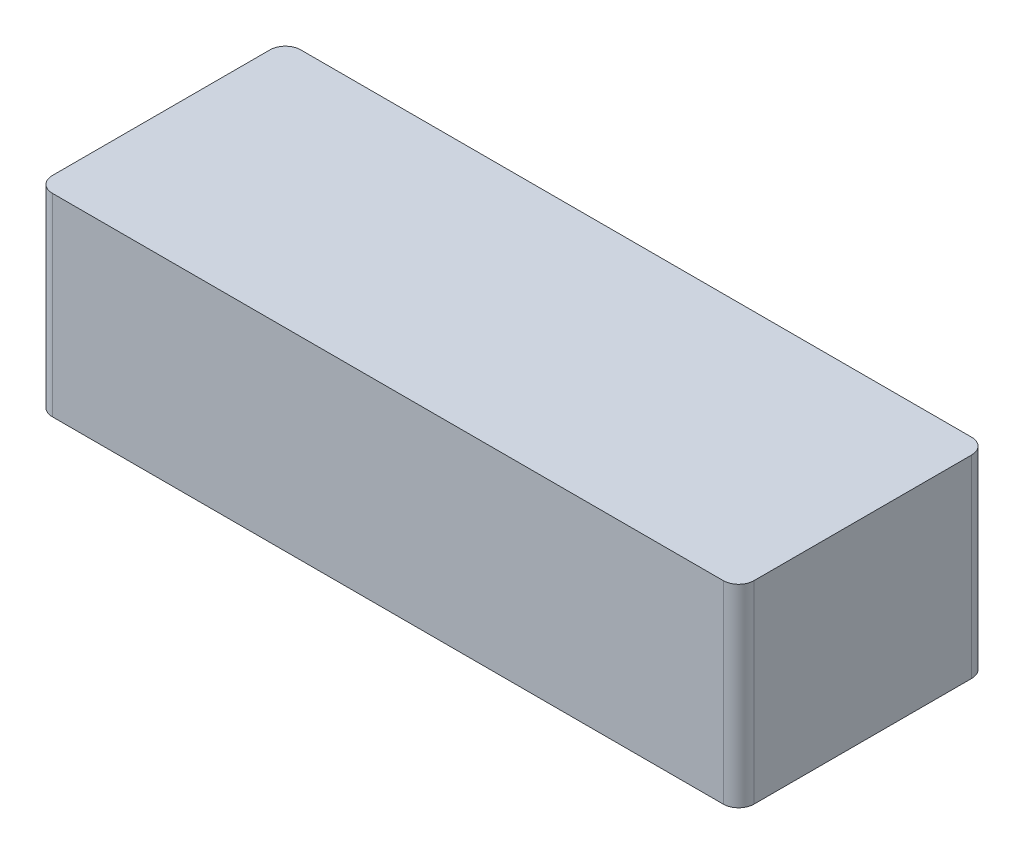
SolidWorks part; units mm, degrees
material "PA Type 6"
ref_plane "Front Plane" through (0, 0, 0) normal (0, 0, 1) x (1, 0, 0)
ref_plane "Top Plane" through (0, 0, 0) normal (0, 1, 0) x (1, 0, 0)
ref_plane "Right Plane" through (0, 0, 0) normal (1, 0, 0) x (0, 0, -1)
sketch "Sketch1" plane through (0, 0, 0) normal (0, 1, 0) x (1, 0, 0)
  line L0 (-68.5, -21.25) -> (-68.5, 21.25)
  line L1 (-65.5, -23.25) -> (65.5, -23.25) construction
  line L2 (-67.5, -21.25) -> (-67.5, 21.25) construction
  line L3 (-65.5, 23.25) -> (65.5, 23.25) construction
  line L4 (67.5, -21.25) -> (67.5, 21.25) construction
  line L5 (-67.5, -23.25) -> (67.5, 23.25) construction
  line L6 (-67.5, 23.25) -> (67.5, -23.25) construction
  line L7 (-65.5, 24.25) -> (65.5, 24.25)
  line L8 (68.5, -21.25) -> (68.5, 21.25)
  line L9 (-65.5, -24.25) -> (65.5, -24.25)
  arc A0 (65.5, 23.25) -> (67.5, 21.25) centre (65.5, 21.25) cw construction
  arc A1 (65.5, -23.25) -> (67.5, -21.25) centre (65.5, -21.25) ccw construction
  arc A2 (-65.5, -23.25) -> (-67.5, -21.25) centre (-65.5, -21.25) cw construction
  arc A3 (-67.5, 21.25) -> (-65.5, 23.25) centre (-65.5, 21.25) cw construction
  arc A4 (-68.5, 21.25) -> (-65.5, 24.25) centre (-65.5, 21.25) cw
  arc A5 (65.5, 24.25) -> (68.5, 21.25) centre (65.5, 21.25) cw
  arc A6 (65.5, -24.25) -> (68.5, -21.25) centre (65.5, -21.25) ccw
  arc A7 (-65.5, -24.25) -> (-68.5, -21.25) centre (-65.5, -21.25) cw
  point P0 (0, 0)
  dimension "D3" = 2
  dimension "D1" = 135
  dimension "D2" = 46.5
  dimension "D4" = 1
extrude "Boss-Extrude1" add sketch "Sketch1" along normal blind 31.5
shell "Shell1" thickness 1
sketch "Sketch2" plane through (0, 0, 0) normal (0, 1, 0) x (1, 0, 0)
  line L0 (-68.5, 21.25) -> (-68.5, 17)
  line L1 (-63.5, 19.25) -> (63.5, 19.25) construction
  line L2 (-63.5, 19.25) -> (-63.5, -19.25) construction
  line L3 (-63.5, -19.25) -> (63.5, -19.25) construction
  line L4 (63.5, 19.25) -> (63.5, -19.25) construction
  line L5 (-63.5, 19.25) -> (63.5, -19.25) construction
  line L6 (-63.5, -19.25) -> (63.5, 19.25) construction
  line L7 (-65.5, 23.25) -> (-61.25, 23.25) construction
  line L8 (-67.5, 21.25) -> (-67.5, 17) construction
  line L9 (-65.5, -23.25) -> (65.5, -23.25) construction
  line L10 (67.5, 21.25) -> (67.5, 17) construction
  line L11 (-67.5, 23.25) -> (67.5, -23.25) construction
  line L12 (-67.5, -23.25) -> (67.5, 23.25) construction
  line L13 (-65.5, -24.25) -> (-61.25, -24.25)
  line L14 (68.5, 21.25) -> (68.5, 17)
  line L15 (-65.5, 24.25) -> (-61.25, 24.25)
  line L16 (-63.5, -17) -> (-68.5, -17)
  line L17 (-61.25, -19.25) -> (-61.25, -24.25)
  line L18 (-65.5, -24.25) -> (65.5, -24.25) construction
  line L19 (-63.5, 17) -> (-68.5, 17)
  line L20 (-61.25, 19.25) -> (-61.25, 24.25)
  line L21 (61.25, 19.25) -> (61.25, 24.25)
  line L22 (63.5, 17) -> (68.5, 17)
  line L23 (61.25, -19.25) -> (61.25, -24.25)
  line L24 (-65.5, -24.25) -> (65.5, -24.25) construction
  line L25 (63.5, -17) -> (68.5, -17)
  line L26 (65.5, -24.25) -> (61.25, -24.25)
  line L27 (68.5, -17) -> (68.5, -21.25)
  line L28 (68.5, 21.25) -> (68.5, -21.25) construction
  line L29 (-68.5, -17) -> (-68.5, -21.25)
  line L30 (-68.5, 21.25) -> (-68.5, -21.25) construction
  line L31 (-67.5, -17) -> (-67.5, -21.25) construction
  line L32 (-67.5, 21.25) -> (-67.5, -21.25) construction
  line L33 (61.25, 24.25) -> (65.5, 24.25)
  line L34 (-65.5, 24.25) -> (65.5, 24.25) construction
  line L35 (61.25, 23.25) -> (65.5, 23.25) construction
  line L36 (-65.5, 23.25) -> (65.5, 23.25) construction
  line L37 (67.5, -17) -> (67.5, -21.25) construction
  line L38 (67.5, 21.25) -> (67.5, -21.25) construction
  arc A0 (-61.25, -19.25) -> (-63.5, -17) centre (-63.5, -19.25) ccw
  arc A1 (63.5, -17) -> (61.25, -19.25) centre (63.5, -19.25) ccw
  arc A2 (61.25, 19.25) -> (63.5, 17) centre (63.5, 19.25) ccw
  arc A3 (-63.5, 17) -> (-61.25, 19.25) centre (-63.5, 19.25) ccw
  arc A4 (65.5, -23.25) -> (67.5, -21.25) centre (65.5, -21.25) ccw construction
  arc A5 (65.5, 23.25) -> (67.5, 21.25) centre (65.5, 21.25) cw construction
  arc A6 (-65.5, 23.25) -> (-67.5, 21.25) centre (-65.5, 21.25) ccw construction
  arc A7 (-67.5, -21.25) -> (-65.5, -23.25) centre (-65.5, -21.25) ccw construction
  arc A8 (-68.5, -21.25) -> (-65.5, -24.25) centre (-65.5, -21.25) ccw
  arc A9 (65.5, -24.25) -> (68.5, -21.25) centre (65.5, -21.25) ccw
  arc A10 (65.5, 24.25) -> (68.5, 21.25) centre (65.5, 21.25) cw
  arc A11 (-65.5, 24.25) -> (-68.5, 21.25) centre (-65.5, 21.25) ccw
  point P0 (0, 0)
  point P9 (0, 0)
  dimension "D3" = 4.5
  dimension "D6" = 2
  dimension "D1" = 127
  dimension "D2" = 38.5
  dimension "D4" = 135
  dimension "D5" = 46.5
  dimension "D7" = 1
extrude "Boss-Extrude2" add sketch "Sketch2" along normal up to surface (30.5 mm away) up to face at (0, 30.5, 0)
sketch "Sketch4" plane through (0, 0, 0) normal (0, 1, 0) x (1, 0, 0)
  line L0 (-68.5, -21.25) -> (-68.5, 21.25)
  line L1 (-65.5, -23.25) -> (65.5, -23.25)
  line L2 (-67.5, -21.25) -> (-67.5, 21.25)
  line L3 (-65.5, 23.25) -> (65.5, 23.25)
  line L4 (67.5, -21.25) -> (67.5, 21.25)
  line L5 (-67.5, -23.25) -> (67.5, 23.25) construction
  line L6 (-67.5, 23.25) -> (67.5, -23.25) construction
  line L7 (-65.5, 24.25) -> (65.5, 24.25)
  line L8 (68.5, -21.25) -> (68.5, 21.25)
  line L9 (-65.5, -24.25) -> (65.5, -24.25)
  arc A0 (65.5, 23.25) -> (67.5, 21.25) centre (65.5, 21.25) cw
  arc A1 (65.5, -23.25) -> (67.5, -21.25) centre (65.5, -21.25) ccw
  arc A2 (-65.5, -23.25) -> (-67.5, -21.25) centre (-65.5, -21.25) cw
  arc A3 (-67.5, 21.25) -> (-65.5, 23.25) centre (-65.5, 21.25) cw
  arc A4 (-68.5, 21.25) -> (-65.5, 24.25) centre (-65.5, 21.25) cw
  arc A5 (65.5, 24.25) -> (68.5, 21.25) centre (65.5, 21.25) cw
  arc A6 (65.5, -24.25) -> (68.5, -21.25) centre (65.5, -21.25) ccw
  arc A7 (-65.5, -24.25) -> (-68.5, -21.25) centre (-65.5, -21.25) cw
  point P0 (0, 0)
  dimension "D3" = 2
  dimension "D1" = 135
  dimension "D2" = 46.5
  dimension "D4" = 1
extrude "Boss-Extrude4" add sketch "Sketch4" against normal blind 6.3
sketch "Sketch5" plane through (0, 0, 0) normal (0, -1, 0) x (1, 0, 0)
  line L1 (-63.5, -19.25) -> (63.5, -19.25) construction
  line L2 (-63.5, -19.25) -> (-63.5, 19.25) construction
  line L3 (-63.5, 19.25) -> (63.5, 19.25) construction
  line L4 (63.5, -19.25) -> (63.5, 19.25) construction
  line L5 (-63.5, -19.25) -> (63.5, 19.25) construction
  line L6 (-63.5, 19.25) -> (63.5, -19.25) construction
  circle A0 centre (-63.5, 19.25) radius 1.5
  circle A1 centre (-63.5, -19.25) radius 1.5
  circle A2 centre (63.5, 19.25) radius 1.5
  circle A3 centre (63.5, -19.25) radius 1.5
  point P0 (0, 0)
  dimension "D3" = 3
  dimension "D1" = 127
  dimension "D2" = 38.5
extrude "Cut-Extrude2" cut sketch "Sketch5" against normal blind 5
